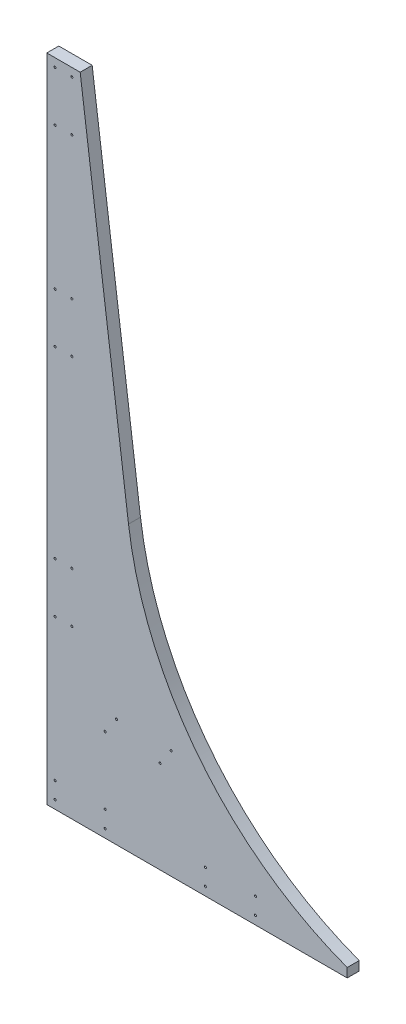
SolidWorks part; units mm, degrees
material "Pine"
ref_plane "Front Plane" through (0, 0, 0) normal (0, 0, 1) x (1, 0, 0)
ref_plane "Top Plane" through (0, 0, 0) normal (0, 1, 0) x (1, 0, 0)
ref_plane "Right Plane" through (0, 0, 0) normal (1, 0, 0) x (0, 0, -1)
sketch "Sketch1" plane through (0, 0, 0) normal (0, 0, 1) x (1, 0, 0)
  line L0 (0, 0) -> (500, 0)
  line L1 (0, 0) -> (0, 990.6)
  line L3 (0, 990.6) -> (50.8, 990.6)
  line L4 (50.8, 990.6) -> (124.3674, 431.8)
  line L7 (457.201, 13.862) -> (457.201, 0)
  arc A9 (124.3674, 431.8) -> (500, 0) centre (638.1166, 499.4364) ccw
  dimension "D18" = 50.8
  dimension "D1" = 500
  dimension "D2" = 990.6
  dimension "D3" = 42.799
  dimension "D4" = 50.8
  dimension "D5" = 558.8
  dimension "D6" = 97.5
extrude "Boss-Extrude1" add sketch "Sketch1" along normal blind 18.2562
sketch "Sketch2" plane through (0, 0, 18.2562) normal (0, 0, 1) x (1, 0, 0)
  line L0 (0, 990.6) -> (50.8, 990.6) construction
  line L1 (0, 0) -> (0, 990.6) construction
  line L2 (12.7, 977.9) -> (38.1, 977.9) construction
  line L3 (38.1, 977.9) -> (38.1, 901.7) construction
  line L4 (38.1, 901.7) -> (12.7, 901.7) construction
  line L5 (12.7, 901.7) -> (12.7, 977.9) construction
  line L6 (12.7, 901.7) -> (12.7, 685.8) construction
  line L7 (12.7, 609.6) -> (38.1, 609.6) construction
  line L8 (12.7, 685.8) -> (12.7, 609.6) construction
  line L9 (38.1, 685.8) -> (12.7, 685.8) construction
  line L10 (12.7, 254) -> (12.7, 38.1) construction
  line L11 (12.7, 254) -> (12.7, 330.2) construction
  line L12 (12.7, 330.2) -> (38.1, 330.2) construction
  line L13 (38.1, 330.2) -> (38.1, 254) construction
  line L14 (38.1, 254) -> (12.7, 254) construction
  line L15 (12.7, 38.1) -> (88.9, 38.1) construction
  line L16 (88.9, 38.1) -> (88.9, 12.7) construction
  line L17 (88.9, 12.7) -> (12.7, 12.7) construction
  line L18 (12.7, 12.7) -> (12.7, 38.1) construction
  line L20 (88.9, 38.1) -> (241.3, 38.1) construction
  line L21 (241.3, 38.1) -> (317.5, 38.1) construction
  line L22 (317.5, 38.1) -> (317.5, 12.7) construction
  line L23 (317.5, 12.7) -> (241.3, 12.7) construction
  line L24 (241.3, 12.7) -> (241.3, 38.1) construction
  circle A0 centre (12.7, 977.9) radius 1.5875
  circle A1 centre (38.1, 977.9) radius 1.5875
  circle A2 centre (12.7, 901.7) radius 1.5875
  circle A3 centre (38.1, 901.7) radius 1.5875
  circle A4 centre (12.7, 609.6) radius 1.5875
  circle A5 centre (38.1, 609.6) radius 1.5875
  circle A6 centre (12.7, 685.8) radius 1.5875
  circle A7 centre (38.1, 685.8) radius 1.5875
  circle A8 centre (12.7, 254) radius 1.5875
  circle A9 centre (38.1, 254) radius 1.5875
  circle A10 centre (12.7, 330.2) radius 1.5875
  circle A11 centre (38.1, 330.2) radius 1.5875
  circle A12 centre (12.7, 38.1) radius 1.5875
  circle A13 centre (12.7, 12.7) radius 1.5875
  circle A14 centre (88.9, 38.1) radius 1.5875
  circle A15 centre (88.9, 12.7) radius 1.5875
  circle A16 centre (241.3, 38.1) radius 1.5875
  circle A17 centre (317.5, 38.1) radius 1.5875
  circle A18 centre (241.3, 12.7) radius 1.5875
  circle A19 centre (317.5, 12.7) radius 1.5875
  dimension "D1" = 3.175
  dimension "D3" = 25.4
  dimension "D4" = 12.7
  dimension "D10" = 279.4
  dimension "D13" = 215.9
  dimension "D2" = 12.7
  dimension "D5" = 76.2
  dimension "D6" = 215.9
  dimension "D7" = 76.2
  dimension "D8" = 25.4
  dimension "D9" = 25.4
  dimension "D11" = 76.2
  dimension "D12" = 25.4
  dimension "D14" = 25.4
  dimension "D15" = 76.2
  dimension "D16" = 25.4
  dimension "D17" = 76.2
  dimension "D18" = 152.4
extrude "Cut-Extrude1" cut sketch "Sketch2" against normal through all
sketch "Sketch3" plane through (0, 0, 18.2562) normal (0, 0, 1) x (1, 0, 0)
  line L0 (88.9, 140.661) -> (172.1104, 140.661) construction
  line L1 (106.1212, 165.426) -> (189.3316, 165.426) construction
  line L2 (0, 0) -> (0, 990.6) construction
  circle A0 centre (88.9, 140.661) radius 1.5875
  circle A1 centre (106.1212, 165.426) radius 1.5875
  circle A2 centre (189.3316, 165.426) radius 1.5875
  circle A3 centre (172.1104, 140.661) radius 1.5875
  dimension "D1" = 3.175
  dimension "D2" = 24.765
  dimension "D3" = 17.2212
  dimension "D4" = 65.9892
  dimension "D5" = 17.2212
  dimension "D6" = 88.9
extrude "Cut-Extrude2" cut sketch "Sketch3" against normal through all
